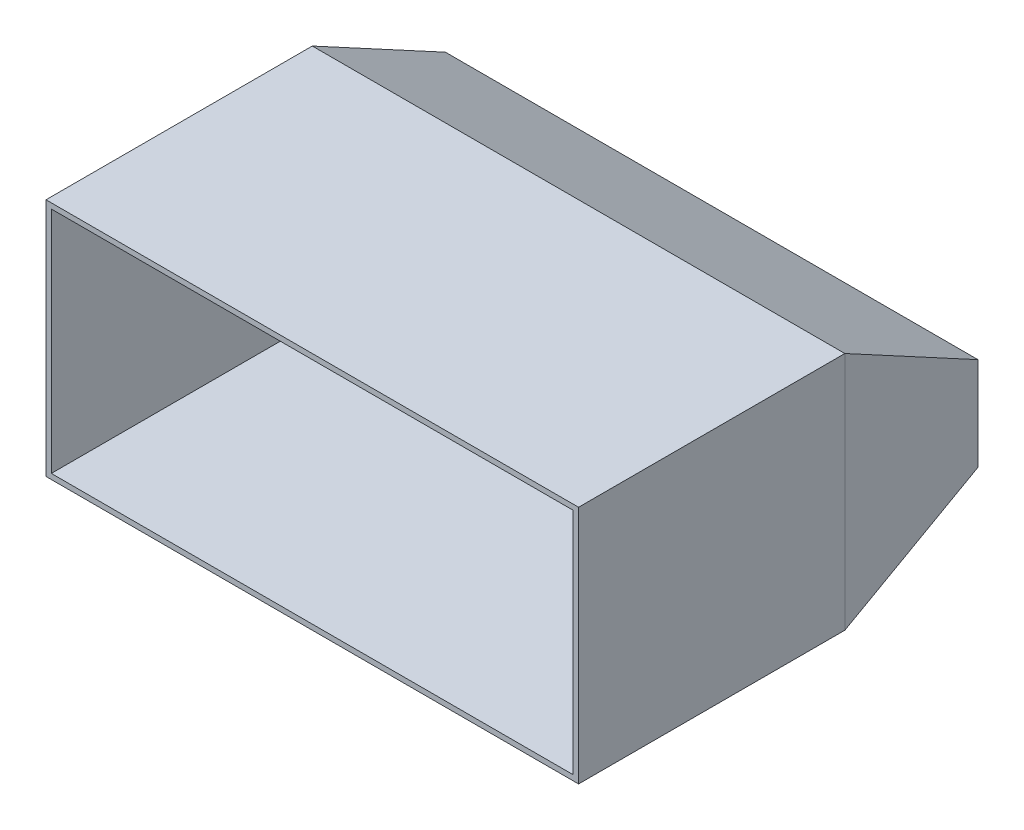
SolidWorks part; units mm, degrees
material "AISI 304"
ref_plane "Front Plane" through (0, 0, 0) normal (0, 0, 1) x (1, 0, 0)
ref_plane "Top Plane" through (0, 0, 0) normal (0, 1, 0) x (1, 0, 0)
ref_plane "Right Plane" through (0, 0, 0) normal (1, 0, 0) x (0, 0, -1)
sketch "Sketch1" plane through (0, 0, 0) normal (0, 0, 1) x (1, 0, 0)
  line L0 (2, -2) -> (2, -88)
  line L1 (0, 0) -> (200, 0)
  line L2 (0, 0) -> (0, -90)
  line L3 (0, -90) -> (200, -90)
  line L4 (200, 0) -> (200, -90)
  line L5 (0, 0) -> (200, -90) construction
  line L6 (0, -90) -> (200, 0) construction
  line L7 (2, -88) -> (198, -88)
  line L8 (198, -2) -> (198, -88)
  line L9 (2, -2) -> (198, -2)
  point P4 (100, -45)
  dimension "D1" = 200
  dimension "D2" = 90
  dimension "D3" = 2
extrude "Boss-Extrude1" add sketch "Sketch1" along normal blind 100
ref_plane "Plane1" through (0, 0, -50) normal (0, 0, 1) x (1, 0, 0)
sketch "Sketch2" plane through (0, 0, 0) normal (0, 0, -1) x (-1, 0, 0)
  line L1 (-200, 0) -> (0, 0)
  line L2 (-200, 0) -> (-200, -90)
  line L3 (-200, -90) -> (0, -90)
  line L4 (0, 0) -> (0, -90)
  line L5 (-200, 0) -> (0, -90) construction
  line L6 (-200, -90) -> (0, 0) construction
  point P4 (-100, -45)
sketch "Sketch3" plane through (0, 0, -50) normal (0, 0, 1) x (1, 0, 0)
  line L0 (200, 0) -> (0, 0) construction
  line L1 (0, -27) -> (200, -27)
  line L2 (0, -27) -> (0, -62)
  line L3 (0, -62) -> (200, -62)
  line L4 (200, -27) -> (200, -62)
  line L5 (0, -27) -> (200, -62) construction
  line L6 (0, -62) -> (200, -27) construction
  line L8 (0, 0) -> (0, -90) construction
  line L9 (200, 0) -> (200, -90) construction
  point P4 (100, -44.5)
  dimension "D1" = 35
  dimension "D2" = 27
  dimension "D3" = 0
  dimension "D4" = 0
surface "Surface-Loft1"
